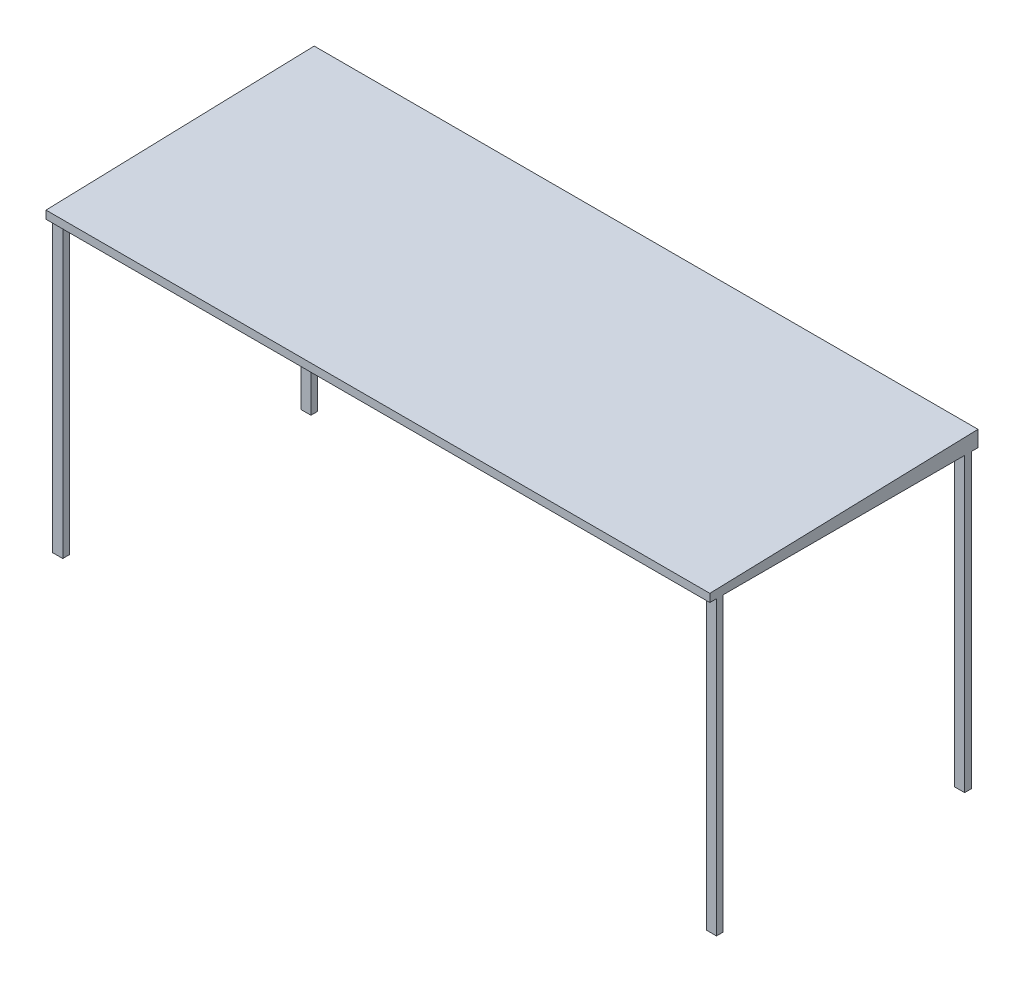
SolidWorks part; units mm, degrees
ref_plane "Alzado" through (0, 0, 0) normal (0, 0, 1) x (1, 0, 0)
ref_plane "Planta" through (0, 0, 0) normal (0, 1, 0) x (1, 0, 0)
ref_plane "Vista lateral" through (0, 0, 0) normal (1, 0, 0) x (0, 0, -1)
sketch "Croquis2" plane through (0, 0, 0) normal (0, 1, 0) x (1, 0, 0)
  line L0 (76.2, 0) -> (2500, 0) construction
  line L1 (0, 0) -> (76.2, 0)
  line L2 (0, 0) -> (0, -50.8)
  line L3 (0, -50.8) -> (76.2, -50.8)
  line L4 (76.2, 0) -> (76.2, -50.8)
  line L5 (2500, 0) -> (2500, -960) construction
  line L6 (2500, -960) -> (0, -960) construction
  line L7 (0, -960) -> (0, -50.8) construction
  line L8 (4923.8, 0) -> (4923.8, -50.8)
  line L9 (5000, -50.8) -> (4923.8, -50.8)
  line L10 (5000, 0) -> (5000, -50.8)
  line L11 (5000, 0) -> (4923.8, 0)
  line L12 (76.2, -1920) -> (2500, -1920) construction
  line L13 (5000, -1920) -> (4923.8, -1920)
  line L14 (5000, -1920) -> (5000, -1869.2)
  line L15 (5000, -1869.2) -> (4923.8, -1869.2)
  line L16 (4923.8, -1920) -> (4923.8, -1869.2)
  line L17 (76.2, -1920) -> (76.2, -1869.2)
  line L18 (0, -1869.2) -> (76.2, -1869.2)
  line L19 (0, -1920) -> (0, -1869.2)
  line L20 (0, -1920) -> (76.2, -1920)
  dimension "D1" = 76.2
  dimension "D2" = 50.8
  dimension "D3" = 2500
  dimension "D4" = 960
extrude "Saliente-Extruir1" add sketch "Croquis2" along normal blind 2200
sketch "Croquis3" plane through (5000, 0, 0) normal (1, 0, 0) x (0, 0, -1)
  line L0 (-1970, 2200) -> (50, 2200)
  line L1 (50, 2200) -> (50, 2320)
  line L2 (50, 2320) -> (-1970, 2260)
  line L3 (-1970, 2260) -> (-1970, 2200)
  line L4 (0, 2200) -> (0, 0) construction
  line L5 (-1920, 2200) -> (-1920, 0) construction
  dimension "D1" = 50
  dimension "D2" = 50
  dimension "D3" = 120
  dimension "D4" = 60
extrude "Saliente-Extruir2" add sketch "Croquis3" against normal up to surface (5000 mm away) up to face at (0, 1100, 25.4)
